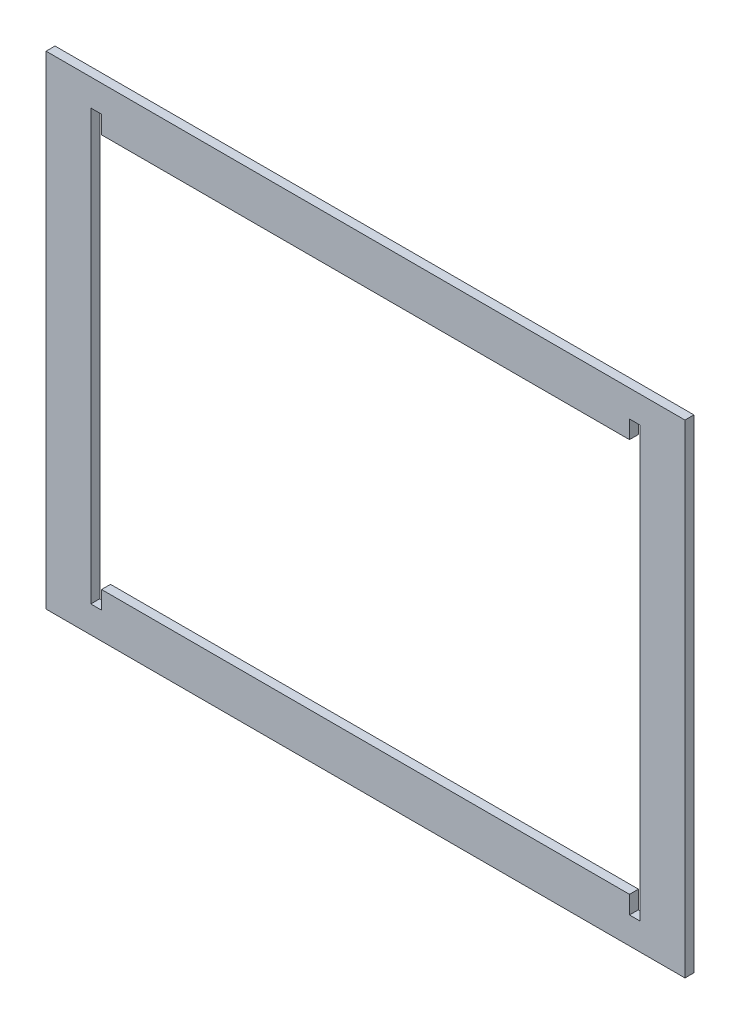
SolidWorks part; units mm, degrees
ref_plane "Front Plane" through (0, 0, 0) normal (0, 0, 1) x (1, 0, 0)
ref_plane "Top Plane" through (0, 0, 0) normal (0, 1, 0) x (1, 0, 0)
ref_plane "Right Plane" through (0, 0, 0) normal (1, 0, 0) x (0, 0, -1)
sketch "Sketch1" plane through (0, 0, 0) normal (0, 0, 1) x (1, 0, 0)
  line L1 (-153.5, -110) -> (153.5, -110)
  line L2 (-153.5, -110) -> (-153.5, 110)
  line L3 (-153.5, 110) -> (153.5, 110)
  line L4 (153.5, -110) -> (153.5, 110)
  line L5 (-153.5, -110) -> (153.5, 110) construction
  line L6 (-153.5, 110) -> (153.5, -110) construction
  line L7 (-178.5, -135) -> (178.5, -135)
  line L8 (-178.5, -135) -> (-178.5, 135)
  line L9 (-178.5, 135) -> (178.5, 135)
  line L10 (178.5, -135) -> (178.5, 135)
  line L11 (-178.5, -135) -> (178.5, 135) construction
  line L12 (-178.5, 135) -> (178.5, -135) construction
  point P0 (0, 0)
  point P6 (0, 0)
  dimension "D1" = 307
  dimension "D2" = 220
  dimension "D3" = 25
  dimension "D4" = 25
extrude "Extrude1" add sketch "Sketch1" along normal blind 5
sketch "Sketch3" plane through (0, 0, 5) normal (0, 0, 1) x (1, 0, 0)
  line L0 (153.5, 110) -> (-153.5, 110) construction
  line L1 (-153.5, 110) -> (-147.5, 110)
  line L2 (-153.5, 110) -> (-153.5, 120)
  line L3 (-153.5, 120) -> (-147.5, 120)
  line L4 (-147.5, 110) -> (-147.5, 120)
  line L5 (147.5, 110) -> (153.5, 110)
  line L6 (147.5, 110) -> (147.5, 120)
  line L7 (147.5, 120) -> (153.5, 120)
  line L8 (153.5, 110) -> (153.5, 120)
  line L9 (-153.5, -110) -> (153.5, -110) construction
  line L10 (147.5, -110) -> (153.5, -110)
  line L11 (147.5, -110) -> (147.5, -120)
  line L12 (147.5, -120) -> (153.5, -120)
  line L13 (153.5, -110) -> (153.5, -120)
  line L15 (-153.5, -110) -> (-147.5, -110)
  line L16 (-153.5, -110) -> (-153.5, -120)
  line L17 (-153.5, -120) -> (-147.5, -120)
  line L18 (-147.5, -110) -> (-147.5, -120)
  line L20 (153.5, -110) -> (153.5, 110) construction
  dimension "D1" = 10
  dimension "D2" = 6
extrude "Cut-Extrude1" cut sketch "Sketch3" against normal through all
